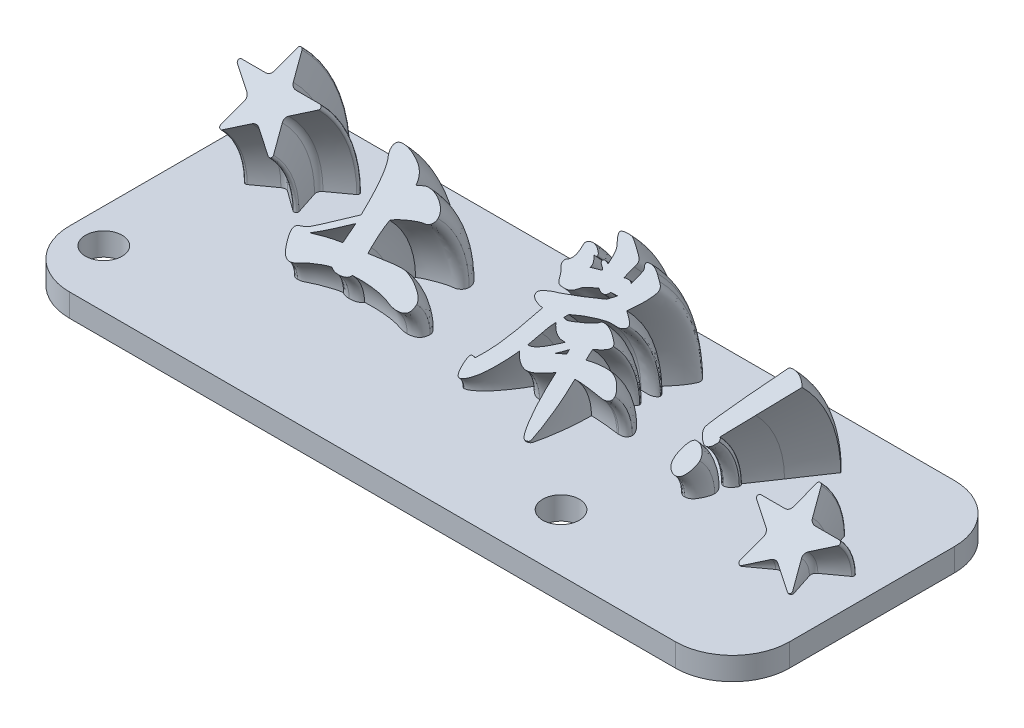
SolidWorks part; units mm, degrees
ref_plane "前视基准面" through (0, 0, 0) normal (0, 0, 1) x (1, 0, 0)
ref_plane "上视基准面" through (0, 0, 0) normal (0, 1, 0) x (1, 0, 0)
ref_plane "右视基准面" through (0, 0, 0) normal (1, 0, 0) x (0, 0, -1)
other "Configuration Table"
sketch "草图1" plane through (0, 0, 0) normal (0, 1, 0) x (1, 0, 0)
  line L1 (-68.5162, -34.4197) -> (58.454, -34.4197)
  line L7 (46.4838, -34.4197) -> (46.4838, -10)
  line L28 (46.4838, -10) -> (-16.5162, -10)
  line L29 (-16.5162, -10) -> (-16.5162, -34.4197)
  circle A1 centre (26.4838, -29.4197) radius 1.6
  circle A2 centre (-13.5162, -29.4197) radius 1.6
  arc A3 (-1.5, 9.8869) -> (1.5, -9.8869) centre (0, 0) ccw construction
  arc A4 (1.5, -9.8869) -> (22.4003, 10.6636) centre (-2.25, 14.8303) ccw construction
  dimension "D1" = 3.2
  dimension "D3" = 20
  dimension "D4" = 3
extrude "凸台-拉伸1" add sketch "草图1" along normal blind 2 contours L28 L29 L1 L7 A2 A1
sketch "草图2" plane through (0, 2, 0) normal (0, 1, 0) x (1, 0, 0)
  line L1 (-12.1811, -18.2912) -> (-11.5287, -16.2832)
  line L5 (22.0913, -12.7548) -> (22.5488, -13.125)
  line L6 (17.6615, -18.0229) -> (17.8594, -18.0655)
  line L7 (35.9173, -14.3825) -> (33.9343, -17.3186)
  line L12 (-7.5615, -18.2912) -> (-8.214, -16.2832)
  line L14 (-13.3009, -14.1213) -> (-11.1895, -14.1213)
  line L16 (-11.8733, -18.5148) -> (-10.1652, -17.2738)
  line L18 (-7.8693, -18.5148) -> (-9.5774, -17.2738)
  line L22 (-8.5531, -14.1213) -> (-6.4418, -14.1213)
  line L23 (-10.714, -13.7758) -> (-10.0615, -11.7678)
  line L24 (-11.7103, -15.7242) -> (-13.4184, -14.4831)
  line L25 (-8.0324, -15.7242) -> (-6.3242, -14.4831)
  line L26 (-9.0287, -13.7758) -> (-9.6811, -11.7678)
  line L27 (38.3925, -25.5763) -> (39.0449, -23.5683)
  line L28 (43.0121, -25.5763) -> (42.3596, -23.5683)
  line L29 (37.2727, -21.4064) -> (39.3841, -21.4064)
  line L30 (38.7002, -25.7999) -> (40.4084, -24.5589)
  line L31 (42.7043, -25.7999) -> (40.9962, -24.5589)
  line L32 (42.0205, -21.4064) -> (44.1318, -21.4064)
  line L33 (39.8596, -21.061) -> (40.5121, -19.0529)
  line L34 (38.8633, -23.0093) -> (37.1552, -21.7683)
  line L35 (42.5412, -23.0093) -> (44.2494, -21.7683)
  line L36 (41.5449, -21.061) -> (40.8925, -19.0529)
  arc A3 (-1.5, 9.8869) -> (1.5, -9.8869) centre (0, 0) ccw construction
  arc A4 (1.5, -9.8869) -> (22.4003, 10.6636) centre (-2.25, 14.8303) ccw construction
  arc A8 (-9.6811, -11.7678) -> (-10.0615, -11.7678) centre (-9.8713, -11.8296) ccw
  arc A9 (-6.3242, -14.4831) -> (-6.4418, -14.1213) centre (-6.4418, -14.3213) ccw
  arc A14 (-7.8693, -18.5148) -> (-7.5615, -18.2912) centre (-7.7518, -18.353) ccw
  arc A15 (-8.0712, -18.3682) -> (-7.6386, -18.0539) centre (-9.8713, -15.4357) ccw construction
  circle A16 centre (-13.5162, -29.4197) radius 1.6 construction
  circle A17 centre (-13.5162, -29.4197) radius 1.6 construction
  arc A18 (-12.1811, -18.2912) -> (-11.8733, -18.5148) centre (-11.9909, -18.353) ccw
  arc A19 (-13.3009, -14.1213) -> (-13.4184, -14.4831) centre (-13.3009, -14.3213) ccw
  arc A20 (-11.5287, -16.2832) -> (-11.7103, -15.7242) centre (-12.0042, -16.1287) ccw
  arc A21 (-9.5774, -17.2738) -> (-10.1652, -17.2738) centre (-9.8713, -17.6783) ccw
  arc A22 (-8.0324, -15.7242) -> (-8.214, -16.2832) centre (-7.7385, -16.1287) ccw
  arc A23 (-8.5531, -14.1213) -> (-9.0287, -13.7758) centre (-8.5531, -13.6213) cw
  arc A24 (-11.1895, -14.1213) -> (-10.714, -13.7758) centre (-11.1895, -13.6213) ccw
  arc A25 (40.8925, -19.0529) -> (40.5121, -19.0529) centre (40.7023, -19.1147) ccw
  arc A26 (44.2494, -21.7683) -> (44.1318, -21.4064) centre (44.1318, -21.6064) ccw
  arc A27 (42.7043, -25.7999) -> (43.0121, -25.5763) centre (42.8218, -25.6381) ccw
  arc A28 (42.5024, -25.6533) -> (42.935, -25.339) centre (40.7023, -22.7208) ccw construction
  arc A29 (38.3925, -25.5763) -> (38.7002, -25.7999) centre (38.5827, -25.6381) ccw
  arc A30 (37.2727, -21.4064) -> (37.1552, -21.7683) centre (37.2727, -21.6064) ccw
  arc A31 (39.0449, -23.5683) -> (38.8633, -23.0093) centre (38.5694, -23.4138) ccw
  arc A32 (40.9962, -24.5589) -> (40.4084, -24.5589) centre (40.7023, -24.9634) ccw
  arc A33 (42.5412, -23.0093) -> (42.3596, -23.5683) centre (42.8351, -23.4138) ccw
  arc A34 (42.0205, -21.4064) -> (41.5449, -21.061) centre (42.0205, -20.9064) cw
  arc A35 (39.3841, -21.4064) -> (39.8596, -21.061) centre (39.3841, -20.9064) ccw
  spline S0 degree 3 poles (2.3526, -20.6378) (2.6893, -20.5978) (3.1672, -20.5437) (3.7687, -20.4792) (4.1391, -20.4442) (4.4551, -20.4122) (4.768, -20.391) (4.975, -20.3766) (5.0951, -20.3761) knots 0 0 0 0 0.369104 0.523602 0.658585 0.774132 0.869353 1 1 1 1
  spline S1 degree 3 poles (5.0951, -20.3761) (5.2231, -20.3785) (5.4181, -20.3904) (5.6741, -20.4493) (5.8708, -20.5059) (6.0683, -20.582) (6.2695, -20.6699) (6.4692, -20.7812) (6.6687, -20.9006) (6.8565, -21.0275) (7.0234, -21.1555) (7.1658, -21.2796) (7.2837, -21.4015) (7.3725, -21.5225) (7.4587, -21.6715) (7.4882, -21.7919) (7.4888, -21.8697) knots 0 0 0 0 0.128375 0.194548 0.262645 0.333219 0.406341 0.482296 0.561956 0.639175 0.709066 0.772472 0.828237 0.878523 0.922396 1 1 1 1
  spline S2 degree 3 poles (7.4888, -21.8697) (7.4864, -22.0089) (7.466, -22.215) (7.3466, -22.4492) (7.2272, -22.5878) (7.07, -22.6904) (6.8053, -22.7968) (6.5788, -22.8154) (6.4228, -22.8165) knots 0 0 0 0 0.258328 0.369682 0.4787 0.59042 0.711456 1 1 1 1
  spline S3 degree 3 poles (6.4228, -22.8165) (6.2718, -22.8186) (6.0457, -22.7911) (5.7463, -22.7224) (5.5192, -22.64) (5.2734, -22.5508) (4.9902, -22.4845) (4.6711, -22.422) (4.3227, -22.3741) (3.9658, -22.3352) (3.6175, -22.3041) (3.2868, -22.2873) (2.9796, -22.2818) (2.7079, -22.2812) (2.4419, -22.2876) (2.268, -22.2902) (2.1696, -22.2974) knots 0 0 0 0 0.104785 0.158054 0.213302 0.272766 0.339916 0.415316 0.49907 0.584472 0.665213 0.742304 0.814868 0.879026 0.931349 1 1 1 1
  spline S4 degree 3 poles (2.1696, -22.2974) (2.1352, -22.3636) (2.0594, -22.4485) (1.9357, -22.5404) (1.8221, -22.5926) (1.6942, -22.6345) (1.4929, -22.6806) (1.3305, -22.6839) (1.2185, -22.6867) knots 0 0 0 0 0.205636 0.313013 0.426887 0.551711 0.687218 1 1 1 1
  spline S5 degree 3 poles (1.2185, -22.6867) (1.084, -22.687) (0.8368, -22.6617) (0.6094, -22.5582) (0.5249, -22.4846) knots 0 0 0 0 0.548932 1 1 1 1
  spline S6 degree 3 poles (0.5249, -22.4846) (0.3633, -22.5073) (0.1008, -22.5658) (-0.2736, -22.6753) (-0.607, -22.7805) (-0.9407, -22.9014) (-1.2524, -23.017) (-1.5226, -23.1391) (-1.7554, -23.2579) (-1.9596, -23.3664) (-2.2012, -23.4577) (-2.3804, -23.4941) (-2.4942, -23.4952) knots 0 0 0 0 0.152923 0.25185 0.365627 0.480679 0.584666 0.677237 0.758427 0.829802 0.89378 1 1 1 1
  spline S7 degree 3 poles (-2.4942, -23.4952) (-2.5719, -23.4958) (-2.6894, -23.4736) (-2.8311, -23.4013) (-2.9337, -23.328) (-3.026, -23.2297) (-3.1171, -23.1142) (-3.1985, -22.9752) (-3.2962, -22.7703) (-3.3989, -22.517) (-3.4926, -22.2313) (-3.5495, -21.98) (-3.5705, -21.7913) (-3.5629, -21.6588) (-3.5437, -21.5725) (-3.5122, -21.4948) (-3.466, -21.4273) (-3.4081, -21.3688) (-3.3357, -21.3221) (-3.2519, -21.2834) (-3.1258, -21.2475) (-2.9695, -21.2071) (-2.7942, -21.151) (-2.6411, -21.0847) (-2.5219, -21.0216) (-2.4205, -20.9585) (-2.3245, -20.8857) (-2.1967, -20.8006) (-2.048, -20.689) (-1.8714, -20.5588) (-1.6719, -20.4061) (-1.4439, -20.2352) (-1.1988, -20.0475) (-0.9485, -19.8534) (-0.7027, -19.6703) (-0.4763, -19.4925) (-0.2633, -19.329) (-0.0648, -19.1771) (0.1716, -18.9991) (0.3392, -18.8677) (0.4462, -18.7846) knots 0 0 0 0 0.031844 0.048123 0.065016 0.083344 0.103267 0.125342 0.149306 0.196463 0.237446 0.272633 0.302163 0.315006 0.326946 0.338303 0.349208 0.360327 0.371877 0.384386 0.39811 0.425593 0.450734 0.473562 0.494016 0.506055 0.522541 0.543464 0.569093 0.598856 0.633569 0.672243 0.715869 0.760312 0.802305 0.841741 0.878496 0.912569 0.944371 1 1 1 1
  spline S8 degree 3 poles (0.4462, -18.7846) (0.4516, -18.5435) (0.4561, -18.1896) (0.4535, -17.7293) (0.4469, -17.4087) (0.4374, -17.105) (0.4191, -16.8178) (0.4006, -16.5468) (0.3783, -16.2919) (0.3473, -16.0538) (0.3161, -15.8323) (0.2812, -15.6275) (0.2369, -15.4402) (0.1946, -15.2673) (0.1278, -15.0699) (0.074, -14.9308) (0.0271, -14.8484) knots 0 0 0 0 0.181391 0.266212 0.346247 0.422578 0.494721 0.56264 0.626924 0.687136 0.743189 0.795198 0.84334 0.887978 0.928971 1 1 1 1
  spline S9 degree 3 poles (0.0271, -14.8484) (-0.0244, -14.755) (-0.099, -14.5682) (-0.1321, -14.3698) (-0.1325, -14.2761) knots 0 0 0 0 0.532751 1 1 1 1
  spline S10 degree 3 poles (-0.1325, -14.2761) (-0.1303, -14.1861) (-0.119, -14.0547) (-0.0512, -13.9005) (0.0226, -13.814) (0.1114, -13.7422) (0.27, -13.6789) (0.402, -13.6602) (0.4951, -13.6633) knots 0 0 0 0 0.269933 0.386339 0.496018 0.606023 0.7235 1 1 1 1
  spline S11 degree 3 poles (0.4951, -13.6633) (0.6124, -13.6663) (0.7928, -13.6779) (1.0324, -13.731) (1.2223, -13.7805) (1.4157, -13.85) (1.614, -13.9329) (1.8165, -14.0321) (2.0212, -14.1414) (2.2177, -14.2641) (2.3934, -14.4023) (2.544, -14.5547) (2.67, -14.7195) (2.7741, -14.8952) (2.8783, -15.1509) (2.9143, -15.3576) (2.9249, -15.4974) knots 0 0 0 0 0.106251 0.162594 0.221704 0.283561 0.348229 0.415914 0.487359 0.557984 0.625083 0.689019 0.751224 0.812154 0.873123 1 1 1 1
  spline S12 degree 3 poles (2.9249, -15.4974) (3.0769, -15.4413) (3.3644, -15.3133) (3.6683, -15.2181) (3.8249, -15.2229) knots 0 0 0 0 0.512616 1 1 1 1
  spline S13 degree 3 poles (3.8249, -15.2229) (4.0404, -15.2211) (4.3647, -15.2769) (4.7697, -15.4516) (5.0087, -15.6024) (5.1849, -15.7424) (5.3042, -15.8509) (5.4034, -15.9656) (5.487, -16.0836) (5.5479, -16.2077) (5.6089, -16.3768) (5.6284, -16.5103) (5.6271, -16.5995) knots 0 0 0 0 0.259868 0.39239 0.531092 0.600059 0.664376 0.725762 0.783085 0.838689 0.892389 1 1 1 1
  spline S14 degree 3 poles (5.6271, -16.5995) (5.6309, -16.6846) (5.6015, -16.8101) (5.5257, -16.9655) (5.4419, -17.0714) (5.3379, -17.163) (5.2129, -17.2359) (5.0668, -17.2819) (4.9308, -17.2971) (4.8091, -17.31) (4.7, -17.3265) (4.5772, -17.3562) (4.4381, -17.3887) (4.2864, -17.4349) (4.1188, -17.4859) (3.9365, -17.5455) (3.6808, -17.6334) (3.375, -17.7476) (2.9625, -17.9275) (2.6857, -18.0764) (2.5292, -18.191) knots 0 0 0 0 0.068874 0.103896 0.14068 0.178496 0.216703 0.258161 0.302707 0.328395 0.358341 0.39282 0.431651 0.475157 0.522497 0.574962 0.632013 0.743631 0.841815 1 1 1 1
  spline S15 degree 3 poles (2.5292, -18.191) (2.4653, -18.5065) (2.3765, -19.1825) (2.3492, -19.8636) (2.3505, -20.2229) knots 0 0 0 0 0.472404 1 1 1 1
  spline S16 degree 3 poles (2.3505, -20.2229) (2.3501, -20.3052) (2.3511, -20.4435) (2.3497, -20.5818) (2.3526, -20.6378) knots 0 0 0 0 0.594828 1 1 1 1
  spline S17 degree 3 poles (0.4313, -19.408) (0.1174, -19.6544) (-0.3379, -20.0075) (-0.9336, -20.4452) (-1.3305, -20.731) (-1.6983, -20.9838) (-1.9958, -21.1806) (-2.1719, -21.2911) (-2.2346, -21.3297) knots 0 0 0 0 0.319631 0.461429 0.592118 0.711401 0.818857 0.877857 0.877857 0.877857 0.877857
  spline S18 degree 3 poles (16.0055, -21.1685) (15.9332, -21.2984) (15.7344, -21.6423) (15.4606, -22.0812) (15.1899, -22.4795) (14.9939, -22.7555) (14.808, -23.0122) (14.625, -23.2433) (14.4492, -23.4521) (14.285, -23.6431) (14.1234, -23.8083) (13.9693, -23.9516) (13.8243, -24.0756) (13.6876, -24.1822) (13.561, -24.2739) (13.4439, -24.3486) (13.3367, -24.4084) (13.2124, -24.4578) (13.1217, -24.4825) (13.0636, -24.4825) knots 0.285583 0.285583 0.285583 0.285583 0.355951 0.473629 0.530443 0.583924 0.633894 0.680518 0.723427 0.763167 0.799737 0.832764 0.862777 0.890049 0.914838 0.936729 0.955811 0.972835 1 1 1 1
  spline S19 degree 3 poles (-2.2346, -21.3297) (-2.1625, -21.3098) (-1.8515, -21.227) (-1.0124, -21.0326) (-0.2355, -20.907) (0.2994, -20.8378) knots 0.15518 0.15518 0.15518 0.15518 0.228625 0.470831 1 1 1 1
  spline S20 degree 3 poles (0.2994, -20.8378) (0.324, -20.6173) (0.3827, -20.142) (0.4102, -19.6639) (0.4313, -19.408) knots 0 0 0 0 0.463531 1 1 1 1
  spline S21 degree 3 poles (20.7551, -14.1314) (20.8039, -13.9914) (20.8706, -13.7938) (20.9513, -13.5462) (20.9949, -13.3974) (21.0325, -13.2738) (21.0577, -13.1745) (21.0744, -13.1) (21.0817, -13.0144) (21.0731, -12.9147) (21.0117, -12.815) (20.9577, -12.7143) (20.9388, -12.6116) (20.9667, -12.518) (21.0491, -12.4728) (21.1632, -12.4498) (21.3159, -12.4423) (21.4962, -12.4604) (21.7712, -12.5441) (21.9631, -12.6658) (22.0913, -12.7548) knots 0 0 0 0 0.153902 0.216537 0.270344 0.314844 0.350559 0.376839 0.393837 0.439863 0.477072 0.513952 0.558519 0.582044 0.609613 0.649791 0.703619 0.767284 0.837171 1 1 1 1
  spline S22 degree 3 poles (22.5488, -13.125) (22.6367, -13.1955) (22.7666, -13.2992) (22.8569, -13.4802) (22.883, -13.6122) (22.8531, -13.7607) (22.7856, -13.936) (22.6766, -14.1487) (22.5275, -14.3976) (22.3372, -14.6815) (22.0025, -15.126) (21.7234, -15.4699) (21.5168, -15.7038) knots 0 0 0 0 0.110127 0.153372 0.192109 0.236892 0.29635 0.372484 0.465913 0.574888 0.700458 1 1 1 1
  spline S23 degree 3 poles (21.5168, -15.7038) (21.6235, -15.7846) (21.7731, -15.9011) (21.953, -16.0561) (22.053, -16.1593) (22.1333, -16.2506) (22.2053, -16.3511) (22.238, -16.4297) (22.2381, -16.4803) knots 0 0 0 0 0.37101 0.525656 0.657757 0.769305 0.86258 1 1 1 1
  spline S24 degree 3 poles (22.2381, -16.4803) (22.2376, -16.5315) (22.1991, -16.6089) (22.1075, -16.6905) (22.0101, -16.7525) (21.8945, -16.8086) (21.7618, -16.8446) (21.6171, -16.8702) (21.337, -16.8703) (21.1065, -16.8592) (20.9275, -16.8612) knots 0 0 0 0 0.101429 0.168993 0.248462 0.336495 0.429917 0.528168 0.635289 1 1 1 1
  spline S25 degree 3 poles (20.9275, -16.8612) (20.849, -16.8608) (20.7228, -16.8743) (20.5417, -16.8966) (20.3784, -16.9287) (20.1954, -16.9628) (19.9955, -17.012) (19.7765, -17.0638) (19.4663, -17.1459) (19.0806, -17.2538) (18.5098, -17.4341) (18.1036, -17.5879) (17.8466, -17.6974) knots 0 0 0 0 0.073276 0.118826 0.170797 0.229012 0.293121 0.363506 0.439692 0.593575 0.738488 1 1 1 1
  spline S26 degree 3 poles (17.8466, -17.6974) (17.7707, -17.8048) (17.699, -17.915) (17.6263, -18.0246) knots 0 0 0 0 0.18527 0.18527 0.18527 0.18527
  spline S27 degree 3 poles (16.7785, -19.5335) (16.6314, -19.893) (16.4752, -20.2495) (16.3039, -20.5984) knots 0 0 0 0 0.184017 0.184017 0.184017 0.184017
  spline S28 degree 3 poles (13.0636, -24.4825) (13.0176, -24.4857) (12.9494, -24.4551) (12.8883, -24.3749) (12.8476, -24.2929) (12.8204, -24.1864) (12.7854, -24.0014) (12.7848, -23.8482) (12.7828, -23.7399) knots 0 0 0 0 0.155982 0.241796 0.346476 0.472039 0.622338 1 1 1 1
  spline S29 degree 3 poles (12.7828, -23.7399) (12.785, -23.6132) (12.785, -23.4346) (12.8208, -23.2179) (12.8467, -23.0935) (12.8883, -22.9978) (12.9461, -22.9058) (13.0154, -22.8664) (13.0636, -22.8697) knots 0 0 0 0 0.388213 0.541688 0.670919 0.774725 0.858834 1 1 1 1
  spline S30 degree 3 poles (13.0636, -22.8697) (13.1331, -22.8738) (13.2242, -22.8718) (13.315, -22.9057) (13.3332, -22.9217) (13.3349, -22.9233) knots 0 0 0 0 0.396091 0.521279 0.534791 0.534791 0.534791 0.534791
  spline S31 degree 3 poles (13.3349, -22.9233) (13.3439, -22.9126) (13.3839, -22.8641) (13.4585, -22.7636) (13.5698, -22.6146) (13.7017, -22.4325) (13.8496, -22.2138) (14.0222, -21.9624) (14.2119, -21.6677) (14.4072, -21.319) (14.6204, -20.9206) (14.848, -20.47) (15.0855, -19.9648) (15.4334, -19.1888) (15.6968, -18.5788) (15.8722, -18.1527) knots 0.031545 0.031545 0.031545 0.031545 0.039044 0.065343 0.098482 0.138773 0.185786 0.239964 0.302164 0.373482 0.454071 0.544318 0.643936 0.753137 1 1 1 1
  spline S32 degree 3 poles (15.8722, -18.1527) (15.724, -18.1301) (15.514, -18.0992) (15.2644, -18.0153) (15.1201, -17.9535) (15.0063, -17.8816) (14.9003, -17.7756) (14.8578, -17.6747) (14.8615, -17.6059) knots 0 0 0 0 0.365188 0.512325 0.638831 0.745897 0.837296 1 1 1 1
  spline S33 degree 3 poles (14.8615, -17.6059) (14.8637, -17.5161) (14.9478, -17.3872) (15.1329, -17.2641) (15.3271, -17.1688) (15.543, -17.0835) (15.7563, -17.0058) (15.9569, -16.9433) (16.123, -16.9054) (16.2627, -16.8751) (16.3897, -16.8424) (16.5391, -16.7999) (16.7127, -16.748) (16.91, -16.6888) (17.1306, -16.6209) (17.3747, -16.5439) (18.2551, -16.2562) (19.051, -15.9827) (19.7488, -15.7144) knots 0 0 0 0 0.048491 0.081973 0.124491 0.170186 0.212642 0.25232 0.28846 0.308521 0.332839 0.362305 0.396052 0.43485 0.478316 0.526072 0.579003 1 1 1 1
  spline S34 degree 2 poles (19.7488, -15.7144) (20.0622, -15.46) (20.3573, -15.1846) knots 0 0 0 1 1 1
  spline S35 degree 3 poles (20.3573, -15.1846) (20.3273, -15.1918) (20.2683, -15.199) (20.1707, -15.1991) (20.0665, -15.2026) (19.9608, -15.2006) (19.8608, -15.2043) (19.7981, -15.2046) (19.7658, -15.2101) knots 0 0 0 0 0.15597 0.299577 0.493419 0.683638 0.834421 1 1 1 1
  spline S36 degree 3 poles (19.7658, -15.2101) (19.7191, -15.3021) (19.6263, -15.4253) (19.4508, -15.5188) (19.312, -15.5335) (19.1765, -15.5234) (19.0062, -15.4773) (18.8937, -15.4098) (18.8296, -15.3527) knots 0 0 0 0 0.279858 0.402463 0.526364 0.651343 0.768537 1 1 1 1
  spline S37 degree 3 poles (18.8296, -15.3527) (18.6443, -15.4209) (18.3956, -15.5241) (18.0948, -15.6423) (17.8976, -15.7297) (17.6861, -15.847) (17.4806, -16.0386) (17.2784, -16.2237) (17.0839, -16.3292) (16.9228, -16.3811) (16.7925, -16.4093) (16.649, -16.4219) (16.5005, -16.4299) (16.3577, -16.4221) (16.2321, -16.4108) (16.1309, -16.3822) (16.045, -16.3463) (15.9777, -16.2793) (15.9186, -16.1866) (15.8621, -16.0638) (15.8111, -15.918) (15.7656, -15.7664) (15.7033, -15.6344) (15.6447, -15.5211) (15.5235, -15.3732) (15.4363, -15.2469) (15.4381, -15.1272) knots 0 0 0 0 0.133001 0.181445 0.217587 0.278392 0.34312 0.406192 0.462628 0.490278 0.520078 0.552264 0.587172 0.620171 0.648558 0.671858 0.69088 0.710487 0.734604 0.764739 0.801314 0.838634 0.871138 0.899586 0.924144 1 1 1 1
  spline S38 degree 3 poles (15.4381, -15.1272) (15.4375, -15.0513) (15.4576, -14.9381) (15.5495, -14.8205) (15.6454, -14.77) (15.7479, -14.7177) (15.8389, -14.63) (15.9252, -14.5228) (16.0019, -14.388) (16.0693, -14.2246) (16.1329, -13.9408) (16.1452, -13.7085) (16.1445, -13.5442) knots 0 0 0 0 0.124996 0.180309 0.237668 0.300608 0.368018 0.442371 0.525622 0.620932 0.730774 1 1 1 1
  spline S39 degree 3 poles (16.1445, -13.5442) (16.1437, -13.4713) (16.1601, -13.3611) (16.2433, -13.2465) (16.3546, -13.1658) (16.5263, -13.1085) (16.7122, -13.0845) (16.8713, -13.0996) (16.9963, -13.1411) (17.1254, -13.2021) (17.2459, -13.2901) (17.3528, -13.3814) (17.4396, -13.4637) (17.4893, -13.5422) (17.5107, -13.6115) (17.5015, -13.6677) (17.4771, -13.7116) (17.4309, -13.7361) (17.3624, -13.7416) (17.3042, -13.7415) (17.2675, -13.7284) (17.2632, -13.7266) knots 0 0 0 0 0.099839 0.14384 0.188415 0.283872 0.385395 0.440454 0.498793 0.562811 0.633168 0.699958 0.753625 0.794155 0.82491 0.849232 0.869496 0.890587 0.916807 0.962121 0.968379 0.968379 0.968379 0.968379
  spline S40 degree 3 poles (17.2632, -13.7266) (17.293, -13.7753) (17.3562, -13.8793) (17.4363, -14.0332) (17.4911, -14.1806) (17.5089, -14.3024) (17.5058, -14.396) (17.4896, -14.462) (17.4675, -14.5044) (17.4485, -14.5161) (17.4418, -14.5183) knots 0.0676 0.0676 0.0676 0.0676 0.247994 0.451212 0.614742 0.741368 0.837725 0.907225 0.957528 0.979754 0.979754 0.979754 0.979754
  spline S41 degree 3 poles (17.4418, -14.5183) (17.4756, -14.5134) (17.5084, -14.5043) (17.5402, -14.491) knots 0.168321 0.168321 0.168321 0.168321 1 1 1 1
  spline S42 degree 2 poles (17.5402, -14.491) (17.9486, -14.37) (18.3679, -14.2952) knots 0 0 0 1 1 1
  spline S43 degree 3 poles (18.3679, -14.2952) (18.3538, -14.2473) (18.2903, -14.1475) (18.1943, -14.0793) (18.1402, -14.0421) knots 0 0 0 0 0.428423 1 1 1 1
  spline S44 degree 3 poles (18.1402, -14.0421) (18.0952, -14.0092) (18.0328, -13.9574) (17.9865, -13.8677) (17.9755, -13.8063) (17.9832, -13.7476) (18.0427, -13.6844) (18.113, -13.68) (18.1573, -13.6782) knots 0 0 0 0 0.310301 0.432464 0.547302 0.650622 0.744603 1 1 1 1
  spline S45 degree 2 poles (18.1573, -13.6782) (18.3433, -13.6897) (18.5083, -13.7782) knots 0 0 0 1 1 1
  spline S46 degree 3 poles (18.5083, -13.7782) (18.5221, -13.57) (18.5286, -13.3139) (18.527, -13.0171) (18.5186, -12.8942) (18.5048, -12.79) (18.482, -12.698) (18.4474, -12.6054) (18.3912, -12.5023) (18.3233, -12.3759) (18.2324, -12.2424) (18.1473, -12.103) (18.0844, -11.9674) (18.048, -11.844) (18.031, -11.7495) (18.0424, -11.6779) (18.0806, -11.6343) (18.1372, -11.5988) (18.2164, -11.5733) (18.3142, -11.549) (18.4888, -11.5311) (18.6299, -11.5215) (18.7317, -11.525) knots 0 0 0 0 0.21327 0.261848 0.303273 0.339157 0.369048 0.400019 0.439899 0.488908 0.546624 0.604812 0.655751 0.698873 0.736102 0.753165 0.770715 0.793236 0.820984 0.855273 0.896187 1 1 1 1
  spline S47 degree 3 poles (18.7317, -11.525) (18.8258, -11.5247) (18.9604, -11.534) (19.1239, -11.5839) (19.2259, -11.6403) (19.3304, -11.715) (19.4573, -11.8027) (19.6098, -11.9126) (19.7785, -12.0376) (19.9472, -12.1635) (20.0923, -12.2832) (20.2083, -12.3859) (20.294, -12.4775) (20.3565, -12.5586) (20.4002, -12.6335) (20.4273, -12.7046) (20.4368, -12.7746) (20.4277, -12.847) (20.4028, -12.9645) (20.3687, -13.0563) (20.3424, -13.1208) knots 0 0 0 0 0.11013 0.156266 0.198539 0.245669 0.306376 0.378837 0.465375 0.551746 0.624764 0.685204 0.732712 0.771172 0.804586 0.833692 0.8596 0.886241 0.918429 1 1 1 1
  spline S48 degree 3 poles (20.3424, -13.1208) (20.2246, -13.4233) (20.1384, -13.7345) (20.084, -14.0544) knots 0 0 0 0 0.980017 0.980017 0.980017 0.980017
  spline S49 degree 3 poles (20.084, -14.0544) (20.0869, -14.0455) (20.1033, -14.0193) (20.168, -13.9925) (20.2682, -13.9798) (20.3972, -13.9733) (20.5289, -13.9821) (20.6668, -14.0111) (20.7432, -14.0741) (20.7551, -14.1314) knots 0.02362 0.02362 0.02362 0.02362 0.059309 0.146768 0.275324 0.457232 0.644965 0.78721 1 1 1 1
  spline S50 degree 3 poles (20.7062, -19.6101) (20.9905, -19.5466) (21.4144, -19.4814) (21.9743, -19.4292) (22.3089, -19.4209) (22.5665, -19.4252) (22.7457, -19.4502) (22.9144, -19.4852) (23.0704, -19.5384) (23.2153, -19.6051) (23.3488, -19.6855) (23.4678, -19.785) (23.6066, -19.9279) (23.7479, -20.1082) (23.9087, -20.3605) (23.9809, -20.5542) (23.9828, -20.6782) knots 0 0 0 0 0.223305 0.328703 0.431011 0.479997 0.526083 0.569511 0.612002 0.652162 0.69172 0.731144 0.770766 0.844341 0.906387 1 1 1 1
  spline S51 degree 3 poles (23.9828, -20.6782) (23.9826, -20.7543) (23.9671, -20.8686) (23.8901, -20.9935) (23.8151, -21.0689) (23.7169, -21.1262) (23.5473, -21.1827) (23.4051, -21.1917) (23.3062, -21.1931) knots 0 0 0 0 0.238234 0.34371 0.449322 0.564588 0.692398 1 1 1 1
  spline S52 degree 2 poles (23.3062, -21.1931) (23.2216, -21.1922) (23.1381, -21.1782) knots 0 0 0 1 1 1
  spline S53 degree 3 poles (23.1381, -21.1782) (22.9755, -21.1462) (22.7005, -21.1137) (22.2966, -21.0688) (21.9276, -21.0353) (21.5582, -21.0039) (21.1491, -20.9774) (20.8687, -20.9681) (20.6998, -20.9718) knots 0 0 0 0 0.202751 0.339071 0.497864 0.656504 0.793166 1 1 1 1
  spline S54 degree 3 poles (20.6998, -20.9718) (20.6969, -21.2854) (20.6863, -21.7426) (20.6504, -22.3331) (20.6194, -22.7433) (20.5738, -23.1487) (20.5249, -23.5671) (20.4568, -24.0041) (20.3957, -24.3769) (20.3472, -24.6702) (20.3074, -24.869) (20.2734, -25.0448) (20.2451, -25.1986) (20.2146, -25.3289) (20.1875, -25.436) (20.1639, -25.5206) (20.1387, -25.6007) (20.0917, -25.6787) (19.9681, -25.7708) (19.8447, -25.7823) (19.7636, -25.7846) knots 0 0 0 0 0.183985 0.268181 0.347068 0.425319 0.507479 0.594157 0.684792 0.729118 0.768532 0.803702 0.834221 0.860262 0.882161 0.899021 0.911784 0.931411 0.9513 1 1 1 1
  spline S55 degree 3 poles (19.7636, -25.7846) (19.7102, -25.7853) (19.6306, -25.7438) (19.5528, -25.6438) (19.4939, -25.5366) (19.4414, -25.3996) (19.3933, -25.2329) (19.3498, -25.0359) (19.296, -24.7327) (19.2463, -24.3287) (19.1983, -23.8315) (19.1705, -23.3239) (19.1644, -22.8187) (19.1664, -22.3378) (19.1773, -21.8007) (19.1903, -21.4275) (19.2083, -21.1995) knots 0 0 0 0 0.03267 0.053646 0.079297 0.109636 0.146036 0.188712 0.236914 0.340293 0.445496 0.552186 0.660971 0.76437 0.8557 1 1 1 1
  spline S56 degree 3 poles (19.2083, -21.1995) (18.9965, -21.3205) (18.6937, -21.498) (18.2906, -21.6899) (18.028, -21.8072) (17.7864, -21.8941) (17.5144, -21.9766) (17.3172, -22.0096) (17.1934, -22.0101) knots 0 0 0 0 0.334274 0.479765 0.611093 0.727818 0.831057 1 1 1 1
  spline S57 degree 3 poles (17.1934, -22.0101) (17.0444, -22.0114) (16.8197, -21.9582) (16.5473, -21.8043) (16.3611, -21.6451) (16.1988, -21.4763) (16.0787, -21.3184) (16.0226, -21.2142) (16.0055, -21.1685) knots 0 0 0 0 0.264872 0.404536 0.555848 0.701143 0.82262 0.910137 0.910137 0.910137 0.910137
  spline S58 degree 3 poles (16.3039, -20.5984) (16.3096, -20.5972) (16.3497, -20.59) (16.4304, -20.5845) (16.5497, -20.5749) (16.6809, -20.5395) (16.8252, -20.4907) (16.9828, -20.4247) (17.1508, -20.3379) (17.3326, -20.2353) (17.5271, -20.1146) (17.7271, -19.979) (17.922, -19.844) (18.0989, -19.717) (18.2542, -19.6082) (18.3832, -19.5112) (18.4913, -19.4333) (18.5862, -19.3571) (18.6459, -19.3075) (18.6743, -19.2761) knots 0.17608 0.17608 0.17608 0.17608 0.181321 0.212676 0.248529 0.288518 0.334215 0.385289 0.441659 0.503801 0.572697 0.647029 0.720668 0.785494 0.84255 0.890805 0.930402 0.962116 1 1 1 1
  spline S59 degree 2 poles (18.6743, -19.2761) (18.5697, -19.2927) (18.4636, -19.291) knots 0 0 0 1 1 1
  spline S60 degree 3 poles (18.4636, -19.291) (18.3117, -19.2923) (18.0835, -19.2483) (17.8098, -19.1044) (17.63, -18.9564) (17.4801, -18.7933) (17.3705, -18.6436) (17.3248, -18.5447) (17.3104, -18.5045) knots 0 0 0 0 0.205149 0.308148 0.415282 0.518483 0.607379 0.665013 0.665013 0.665013 0.665013
  spline S61 degree 3 poles (17.8594, -18.0655) (17.9225, -18.0638) (18.0266, -18.0477) (18.1774, -18.014) (18.3196, -17.9725) (18.4819, -17.9209) (18.6647, -17.8599) (18.8668, -17.7839) (19.0831, -17.7027) (19.2968, -17.6157) (19.4948, -17.5329) (19.6698, -17.4568) (19.8204, -17.3852) (19.9467, -17.3181) (20.0737, -17.2487) (20.1515, -17.1895) (20.1934, -17.1506) knots 0 0 0 0 0.074782 0.124859 0.183532 0.250677 0.32714 0.412435 0.507098 0.601591 0.686553 0.762002 0.828323 0.884473 0.93202 1 1 1 1
  spline S62 degree 2 poles (20.1934, -17.1506) (20.3178, -17.0498) (20.4785, -17.0548) knots 0 0 0 1 1 1
  spline S63 degree 3 poles (20.4785, -17.0548) (20.6471, -17.052) (20.9032, -17.1129) (21.2283, -17.2719) (21.4286, -17.4124) (21.5842, -17.5339) (21.687, -17.6228) (21.7763, -17.7031) (21.8465, -17.7802) (21.9022, -17.8504) (21.9545, -17.9284) (21.9741, -17.9906) (21.9764, -18.0293) knots 0 0 0 0 0.267582 0.415335 0.577185 0.658038 0.731305 0.79477 0.850214 0.897909 0.938224 1 1 1 1
  spline S64 degree 3 poles (21.9764, -18.0293) (21.9756, -18.0966) (21.9171, -18.1937) (21.7988, -18.309) (21.6614, -18.4064) (21.4866, -18.5066) (21.1822, -18.6599) (20.9277, -18.7606) (20.7466, -18.8314) knots 0 0 0 0 0.127558 0.216833 0.326262 0.459552 0.615138 1 1 1 1
  spline S65 degree 3 poles (20.7466, -18.8314) (20.7295, -18.9285) (20.71, -19.1882) (20.705, -19.4483) (20.7062, -19.6101) knots 0 0 0 0 0.378279 1 1 1 1
  spline S66 degree 2 poles (19.2083, -19.8846) (19.208, -19.7239) (19.2147, -19.5633) knots 0 0 0 1 1 1
  spline S67 degree 3 poles (19.2147, -19.5633) (19.0417, -19.7182) (18.7842, -19.9318) (18.5146, -20.1317) (18.4294, -20.1905) (18.4283, -20.1913) knots 0 0 0 0 0.340857 0.490554 0.492611 0.492611 0.492611 0.492611
  spline S68 degree 3 poles (18.4283, -20.1913) (18.4486, -20.1834) (18.709, -20.0822) (18.9686, -19.9788) (19.2083, -19.8846) knots 0.538277 0.538277 0.538277 0.538277 0.574274 1 1 1 1
  spline S69 degree 2 poles (34.3109, -13.7527) (34.474, -13.6879) (34.6492, -13.6846) knots 0 0 0 1 1 1
  spline S70 degree 3 poles (34.6492, -13.6846) (34.7706, -13.6851) (34.9529, -13.7034) (35.1829, -13.7795) (35.3473, -13.8555) (35.502, -13.9557) (35.7047, -14.12) (35.8363, -14.2724) (35.9173, -14.3825) knots 0 0 0 0 0.242277 0.361119 0.481207 0.601916 0.727464 1 1 1 1
  spline S71 degree 3 poles (33.9343, -17.3186) (33.6573, -17.7226) (33.1356, -18.4755) (32.6321, -19.2406) (32.396, -19.5952) knots 0 0 0 0 0.534812 1 1 1 1
  spline S72 degree 3 poles (32.396, -19.5952) (32.4424, -19.5943) (32.5265, -19.6803) (32.5198, -19.7974) (32.5258, -19.8612) knots 0 0 0 0 0.386734 1 1 1 1
  spline S73 degree 3 poles (32.5258, -19.8612) (32.5193, -19.9133) (32.4795, -20.0005) (32.3913, -20.1191) (32.3019, -20.2411) (32.1923, -20.3574) (32.0305, -20.4753) (31.8872, -20.5132) (31.7939, -20.5123) knots 0 0 0 0 0.149931 0.272064 0.426888 0.586197 0.73165 1 1 1 1
  spline S74 degree 3 poles (31.7939, -20.5123) (31.7078, -20.5107) (31.5772, -20.454) (31.4209, -20.3217) (31.2949, -20.1836) (31.18, -20.0307) (31.072, -19.8337) (31.0274, -19.6805) (31.0279, -19.5803) knots 0 0 0 0 0.196985 0.323024 0.476637 0.633076 0.768768 1 1 1 1
  spline S75 degree 3 poles (31.0279, -19.5803) (31.0336, -19.5192) (31.0751, -19.4121) (31.1484, -19.2443) (31.2377, -19.0572) (31.3566, -18.8326) (31.4959, -18.5664) (31.6626, -18.2614) (31.8572, -17.9181) (32.0727, -17.532) (32.3186, -17.1101) (32.5871, -16.6464) (32.8814, -16.1438) (33.205, -15.6031) (33.6776, -14.798) (34.0541, -14.1796) (34.3109, -13.7527) knots 0 0 0 0 0.027228 0.051133 0.082113 0.120054 0.164965 0.216717 0.275752 0.341761 0.414785 0.494509 0.581803 0.675686 0.776817 1 1 1 1
  spline S76 degree 3 poles (31.9896, -21.491) (31.9895, -21.6435) (31.9389, -21.8822) (31.8191, -22.2058) (31.7121, -22.4267) (31.6103, -22.6008) (31.5307, -22.7199) (31.4422, -22.818) (31.3512, -22.9004) (31.2539, -22.9629) (31.1196, -23.0234) (31.0111, -23.0435) (30.9385, -23.0421) knots 0 0 0 0 0.224508 0.358803 0.510592 0.58736 0.657601 0.722346 0.782642 0.838893 0.892982 1 1 1 1
  spline S77 degree 3 poles (30.9385, -23.0421) (30.8439, -23.0417) (30.6996, -23.0127) (30.5284, -22.9136) (30.4089, -22.8128) (30.3056, -22.6881) (30.2054, -22.4854) (30.1818, -22.3132) (30.1811, -22.1974) knots 0 0 0 0 0.2251 0.341415 0.467098 0.59538 0.723607 1 1 1 1
  spline S78 degree 3 poles (30.1811, -22.1974) (30.1782, -22.0171) (30.2183, -21.7416) (30.3214, -21.3754) (30.4105, -21.1397) (30.4965, -20.9593) (30.5623, -20.8381) (30.6317, -20.7352) (30.7062, -20.6521) (30.7816, -20.5865) (30.8828, -20.5225) (30.9694, -20.503) (31.0258, -20.5038) knots 0 0 0 0 0.266514 0.410774 0.563994 0.639776 0.707133 0.76843 0.823574 0.872083 0.916481 1 1 1 1
  spline S79 degree 3 poles (31.0258, -20.5038) (31.1538, -20.5049) (31.3489, -20.5427) (31.5719, -20.6834) (31.7138, -20.8257) (31.834, -20.984) (31.9488, -21.2008) (31.9917, -21.3756) (31.9896, -21.491) knots 0 0 0 0 0.25418 0.381541 0.51654 0.649886 0.773574 1 1 1 1
  spline S80 degree 2 poles (17.6263, -18.0246) (17.6443, -18.0236) (17.6615, -18.0229) knots 0.983401 0.983401 0.983401 1 1 1
  spline S81 degree 3 poles (17.3104, -18.5045) (17.2927, -18.5326) (17.2536, -18.5947) (17.1959, -18.686) (17.0152, -18.9899) (16.8825, -19.2752) (16.7785, -19.5335) knots 0.455102 0.455102 0.455102 0.455102 0.501943 0.558504 0.607344 1 1 1 1
  point P336 (-7.3713, -18.8766)
  point P339 (-12.3713, -18.8766)
  point P364 (-11.4164, -15.9377)
  point P554 (-8.9164, -14.1213)
  point P681 (-10.8262, -14.1213)
  dimension "D1" = 5
  dimension "D2" = 0.2
  dimension "D3" = 0.5
  dimension "D4" = 0.2
  dimension "D5" = 0.5
sketch "草图3" plane through (0, 0, 0) normal (1, 0, 0) x (0, 0, -1)
  line L0 (-10.9197, 2) -> (-25.9197, 2) construction
  line L1 (-25.9197, 2) -> (-15.3131, 12.6066) construction
  line L5 (-34.4197, 2) -> (-10, 2) construction
  line L6 (-34.4197, 2) -> (-34.4197, 0) construction
  arc A0 (-10.9197, 2) -> (-15.3131, 12.6066) centre (-25.9197, 2) ccw
  point P0 (-25.7846, 2)
  point P5 (-23.9907, 2)
  dimension "D1" = 45
  dimension "D2" = 15
  dimension "D3" = 8.5
sweep "扫描3" add profiles "草图2" path "草图3"
fillet "圆角1" radius 5 4 edges at (46.4838, 1, 34.4197) (46.4838, 1, 10) (-16.5162, 1, 10) (-16.5162, 1, 34.4197)
